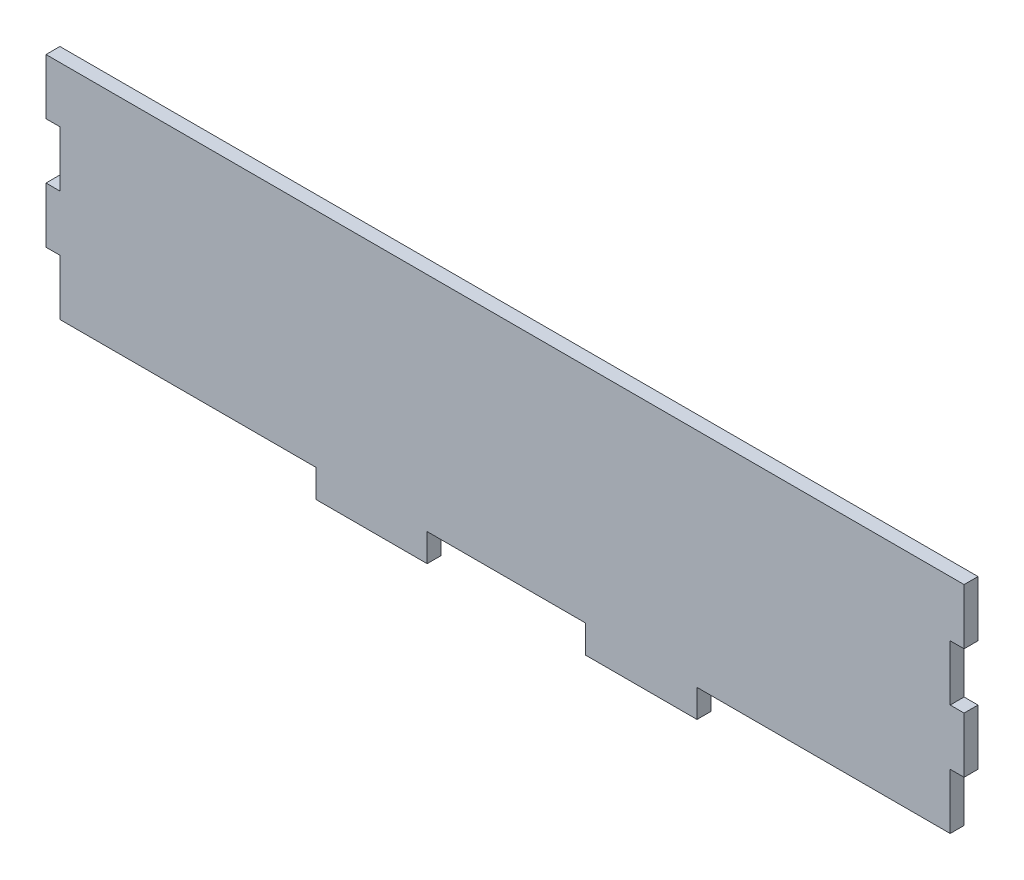
SolidWorks part; units mm, degrees
ref_plane "Front Plane" through (0, 0, 0) normal (0, 0, 1) x (1, 0, 0)
ref_plane "Top Plane" through (0, 0, 0) normal (0, 1, 0) x (1, 0, 0)
ref_plane "Right Plane" through (0, 0, 0) normal (1, 0, 0) x (0, 0, -1)
sketch "Sketch1" plane through (0, 0, 0) normal (0, 0, 1) x (1, 0, 0)
  line L1 (-101.6, -50.8) -> (101.6, -50.8)
  line L2 (-101.6, -50.8) -> (-101.6, 50.8)
  line L3 (-101.6, 50.8) -> (101.6, 50.8)
  line L4 (101.6, -50.8) -> (101.6, 50.8)
  line L5 (-101.6, -50.8) -> (101.6, 50.8) construction
  line L6 (-101.6, 50.8) -> (101.6, -50.8) construction
  point P0 (0, 0)
  dimension "D1" = 203.2
  dimension "D2" = 101.6
extrude "Boss-Extrude1" add sketch "Sketch1" along normal blind 3.175
sketch "Sketch2" plane through (0, 0, 3.175) normal (0, 0, 1) x (1, 0, 0)
  line L0 (-101.6, 25.4) -> (-104.775, 25.4)
  line L1 (-101.6, 50.8) -> (-104.775, 50.8)
  line L2 (-101.6, 50.8) -> (-101.6, 38.1)
  line L3 (-101.6, 38.1) -> (-104.775, 38.1)
  line L4 (-104.775, 50.8) -> (-104.775, 38.1)
  line L5 (-101.6, 25.4) -> (-101.6, 12.7)
  line L6 (-101.6, 12.7) -> (-104.775, 12.7)
  line L7 (-104.775, 25.4) -> (-104.775, 12.7)
  line L8 (-101.6, 0) -> (-104.775, 0)
  line L9 (-101.6, 0) -> (-101.6, -12.7)
  line L10 (-101.6, -12.7) -> (-104.775, -12.7)
  line L11 (-104.775, 0) -> (-104.775, -12.7)
  line L12 (-101.6, -25.4) -> (-104.775, -25.4)
  line L13 (-101.6, -25.4) -> (-101.6, -38.1)
  line L14 (-101.6, -38.1) -> (-104.775, -38.1)
  line L15 (-104.775, -25.4) -> (-104.775, -38.1)
  line L16 (-101.6, -50.8) -> (101.6, -50.8) construction
  line L17 (-79.375, -50.8) -> (-104.775, -50.8)
  line L18 (-79.375, -50.8) -> (-79.375, -57.15)
  line L19 (-79.375, -57.15) -> (-104.775, -57.15)
  line L20 (-104.775, -50.8) -> (-104.775, -57.15)
  line L21 (-17.78, -50.8) -> (-43.18, -50.8)
  line L22 (-17.78, -50.8) -> (-17.78, -57.15)
  line L23 (-17.78, -57.15) -> (-43.18, -57.15)
  line L24 (-43.18, -50.8) -> (-43.18, -57.15)
  line L25 (43.815, -50.8) -> (18.415, -50.8)
  line L26 (43.815, -50.8) -> (43.815, -57.15)
  line L27 (43.815, -57.15) -> (18.415, -57.15)
  line L28 (18.415, -50.8) -> (18.415, -57.15)
  line L29 (105.41, -50.8) -> (80.01, -50.8)
  line L30 (105.41, -50.8) -> (105.41, -57.15)
  line L31 (105.41, -57.15) -> (80.01, -57.15)
  line L32 (80.01, -50.8) -> (80.01, -57.15)
  line L33 (101.6, -50.8) -> (101.6, 50.8) construction
  line L34 (0, 0) -> (0, 50.8) construction
  line L35 (101.6, 50.8) -> (-101.6, 50.8) construction
  line L36 (104.775, -25.4) -> (104.775, -38.1)
  line L37 (101.6, -38.1) -> (104.775, -38.1)
  line L38 (101.6, -25.4) -> (101.6, -38.1)
  line L39 (101.6, -25.4) -> (104.775, -25.4)
  line L40 (104.775, 0) -> (104.775, -12.7)
  line L41 (101.6, -12.7) -> (104.775, -12.7)
  line L42 (101.6, 0) -> (101.6, -12.7)
  line L43 (101.6, 0) -> (104.775, 0)
  line L44 (104.775, 25.4) -> (104.775, 12.7)
  line L45 (101.6, 12.7) -> (104.775, 12.7)
  line L46 (101.6, 25.4) -> (101.6, 12.7)
  line L47 (104.775, 50.8) -> (104.775, 38.1)
  line L48 (101.6, 38.1) -> (104.775, 38.1)
  line L49 (101.6, 50.8) -> (101.6, 38.1)
  line L50 (101.6, 50.8) -> (104.775, 50.8)
  line L51 (101.6, 25.4) -> (104.775, 25.4)
  dimension "D1" = 3.175
  dimension "D2" = 12.7
  dimension "D4" = 6.35
  dimension "D5" = 25.4
  dimension "D7" = 61.595
  dimension "D8" = 3.81
  dimension "D3" = 4
  dimension "D6" = 4
extrude "Boss-Extrude2" add sketch "Sketch2" against normal blind 3.175
sketch "Sketch3" plane through (0, 0, 3.175) normal (0, 0, 1) x (1, 0, 0)
  line L1 (-79.375, -50.8) -> (-104.775, -50.8)
  line L2 (-79.375, -50.8) -> (-79.375, -57.15)
  line L3 (-79.375, -57.15) -> (-104.775, -57.15)
  line L4 (-104.775, -50.8) -> (-104.775, -57.15)
  line L5 (80.01, -50.8) -> (105.41, -50.8)
  line L6 (80.01, -50.8) -> (80.01, -57.15)
  line L7 (80.01, -57.15) -> (105.41, -57.15)
  line L8 (105.41, -50.8) -> (105.41, -57.15)
extrude "Cut-Extrude1" cut sketch "Sketch3" against normal through all
sketch "Sketch4" plane through (0, 0, 3.175) normal (0, 0, 1) x (1, 0, 0)
  line L0 (-17.78, -50.8) -> (18.415, -50.8) construction
  line L1 (-130.8396, 66.4682) -> (114.6355, 66.4682)
  line L2 (-130.8396, 66.4682) -> (-130.8396, 0)
  line L3 (-130.8396, 0) -> (114.6355, 0)
  line L4 (114.6355, 66.4682) -> (114.6355, 0)
  dimension "D1" = 50.8
extrude "Cut-Extrude2" cut sketch "Sketch4" against normal through all
